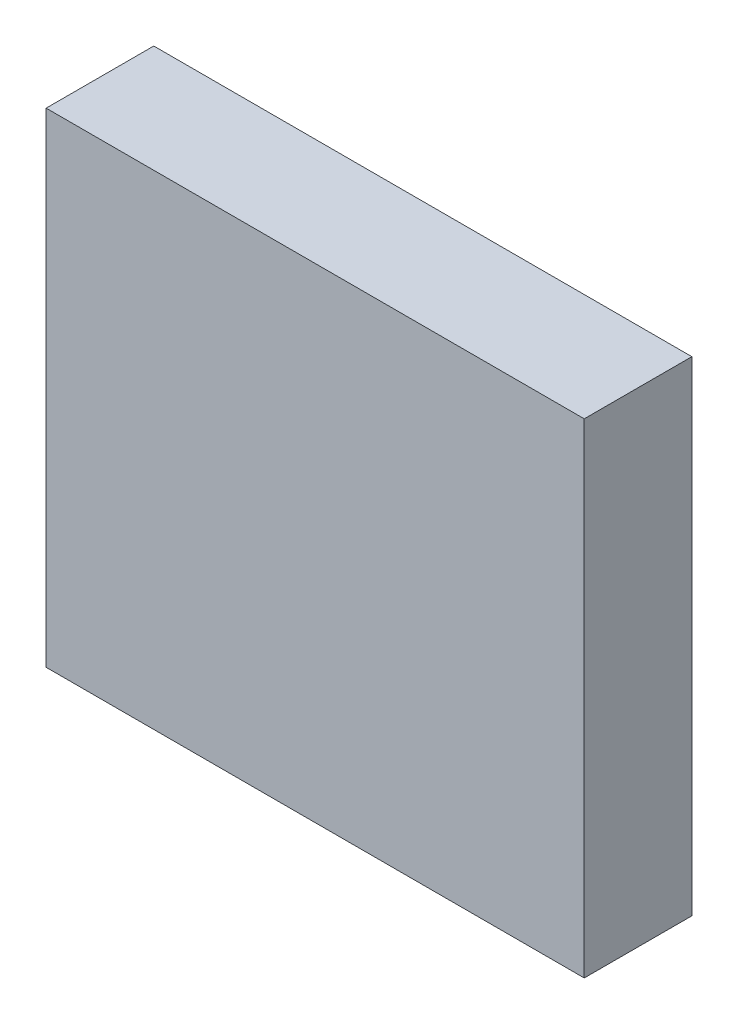
SolidWorks part; units mm, degrees
material "PMMA"
ref_plane "Plan de face" through (0, 0, 0) normal (0, 0, 1) x (1, 0, 0)
ref_plane "Plan de dessus" through (0, 0, 0) normal (0, 1, 0) x (1, 0, 0)
ref_plane "Plan de droite" through (0, 0, 0) normal (1, 0, 0) x (0, 0, -1)
sketch "Esquisse1" plane through (0, 0, 0) normal (0, 0, 1) x (1, 0, 0)
  line L1 (-7.5, -6.75) -> (7.5, -6.75)
  line L2 (-7.5, -6.75) -> (-7.5, 6.75)
  line L3 (-7.5, 6.75) -> (7.5, 6.75)
  line L4 (7.5, -6.75) -> (7.5, 6.75)
  line L5 (-7.5, -6.75) -> (7.5, 6.75) construction
  line L6 (-7.5, 6.75) -> (7.5, -6.75) construction
  point P0 (0, 0)
  dimension "D1" = 13.5
  dimension "D2" = 15
extrude "Boss.-Extru.1" add sketch "Esquisse1" along normal blind 3
